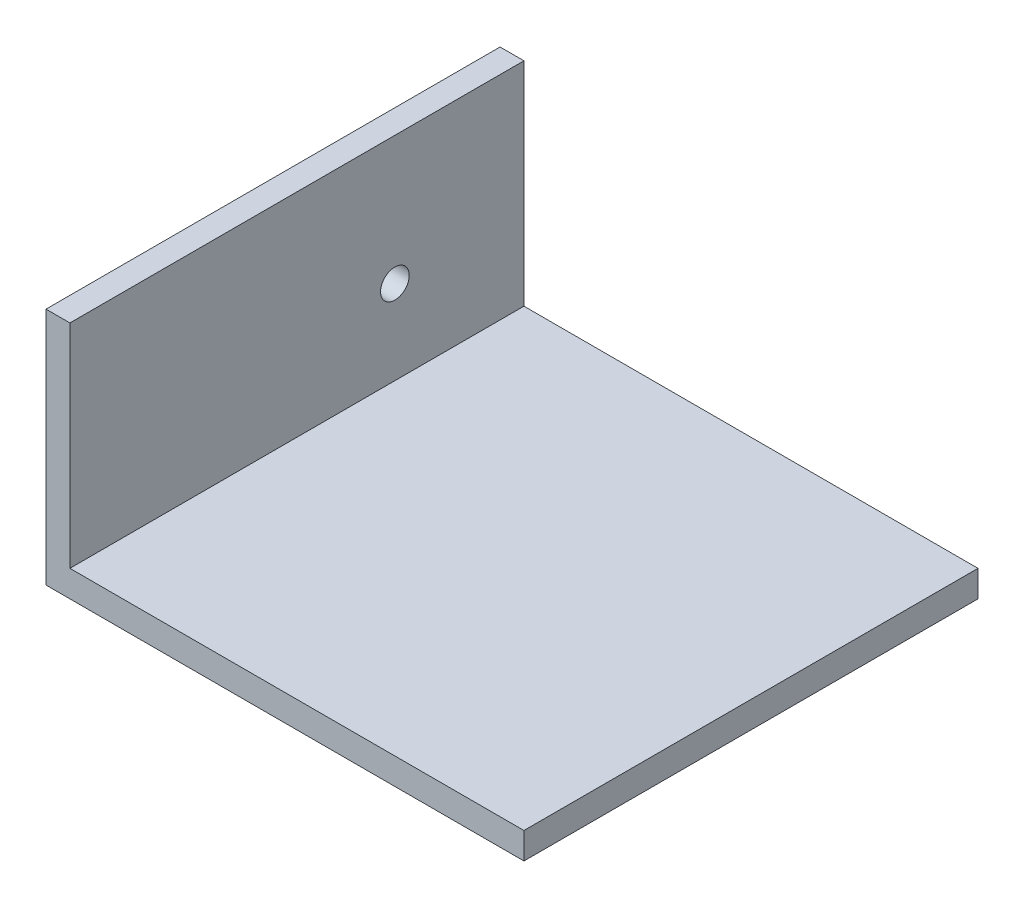
SolidWorks part; units mm, degrees
ref_plane "前视基准面" through (0, 0, 0) normal (0, 0, 1) x (1, 0, 0)
ref_plane "上视基准面" through (0, 0, 0) normal (0, 1, 0) x (1, 0, 0)
ref_plane "右视基准面" through (0, 0, 0) normal (1, 0, 0) x (0, 0, -1)
other "Configuration Table"
sketch "草图1" plane through (0, 0, 0) normal (0, 0, 1) x (1, 0, 0)
  line L0 (-43.5503, 35.6591) -> (-38.5503, 35.6591)
  line L1 (-38.5503, -8.8068) -> (-38.5503, 35.6591)
  line L2 (-38.5503, -8.8068) -> (56.4497, -8.8068)
  line L3 (56.4497, -8.8068) -> (56.4497, -14.3409)
  line L4 (56.4497, -14.3409) -> (-43.5503, -14.3409)
  line L5 (-43.5503, -14.3409) -> (-43.5503, 35.6591)
extrude "凸台-拉伸1" add sketch "草图1" along normal blind 95
sketch "草图2" plane through (-43.5503, 0, 0) normal (-1, 0, 0) x (0, 0, 1)
  circle A0 centre (27, 8.8) radius 3
extrude "切除-拉伸1" cut sketch "草图2" against normal up to next
